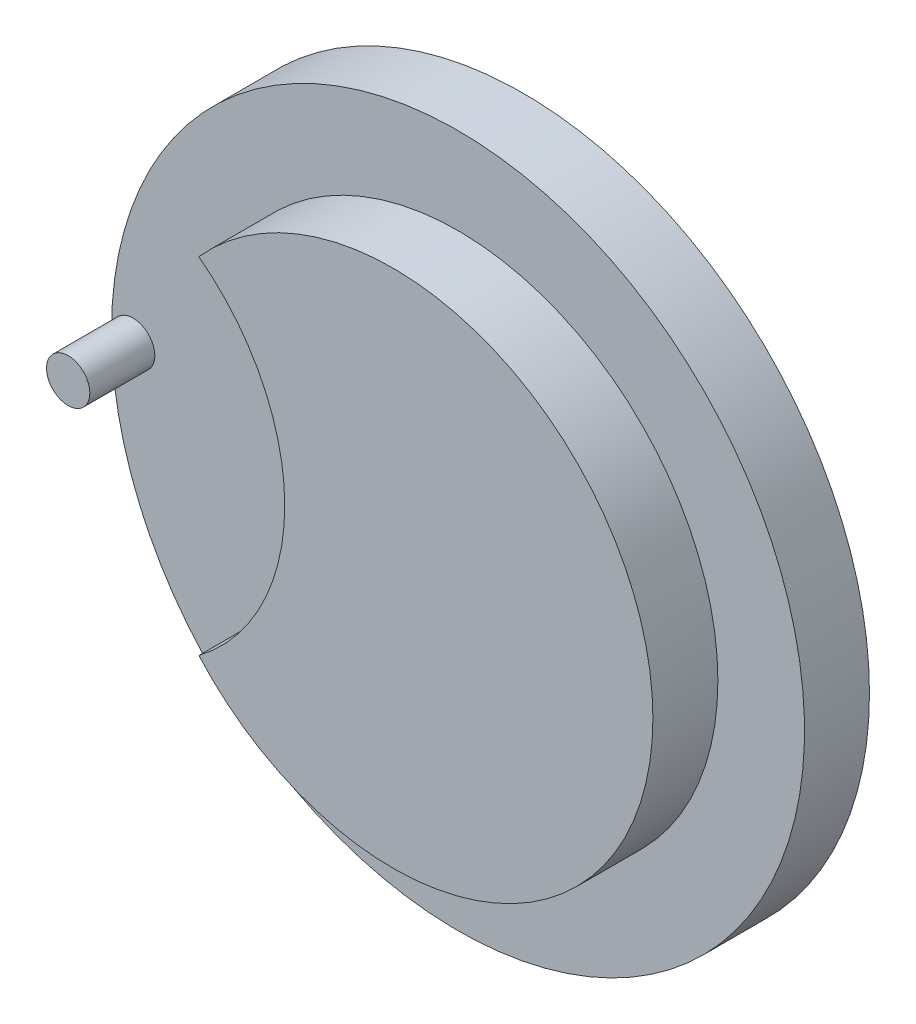
SolidWorks part; units mm, degrees
ref_plane "Front Plane" through (0, 0, 0) normal (0, 0, 1) x (1, 0, 0)
ref_plane "Top Plane" through (0, 0, 0) normal (0, 1, 0) x (1, 0, 0)
ref_plane "Right Plane" through (0, 0, 0) normal (1, 0, 0) x (0, 0, -1)
sketch "Sketch1" plane through (0, 0, 0) normal (0, 0, 1) x (1, 0, 0)
  circle A0 centre (0, 0) radius 50.8
  dimension "D1" = 101.6
extrude "Boss-Extrude1" add sketch "Sketch1" along normal blind 9.525
sketch "Sketch2" plane through (0, 0, 9.525) normal (0, 0, 1) x (1, 0, 0)
  line L0 (0, 0) -> (-84.1375, 0) construction
  circle A0 centre (0, 0) radius 38.1
  circle A3 centre (-47.625, 0) radius 3.175
  arc A4 (-28.4692, -25.3203) -> (-28.4692, 25.3203) centre (-47.625, 0) ccw
  dimension "D1" = 76.2
  dimension "D2" = 6.35
  dimension "D4" = 47.625
  dimension "D5" = 31.75
  dimension "D3" = 84.1375
extrude "Boss-Extrude2" add sketch "Sketch2" along normal blind 9.525
sketch "Sketch7" plane through (0, 0, 0) normal (0, 0, -1) x (-1, 0, 0)
  line L1 (-2.54, 0) -> (2.54, 0)
  line L2 (-2.54, 0) -> (-2.54, 10.16)
  line L3 (-2.54, 10.16) -> (2.54, 10.16)
  line L4 (2.54, 0) -> (2.54, 10.16)
  circle A0 centre (0, 0) radius 4.7625
  point P7 (0, 0)
  dimension "D1" = 9.525
  dimension "D2" = 5.08
  dimension "D3" = 10.16
  dimension "D4" = 2.54
extrude "Cut-Extrude10" cut sketch "Sketch7" against normal blind 9.525 contours A0 | L2 L1 L4 L3
